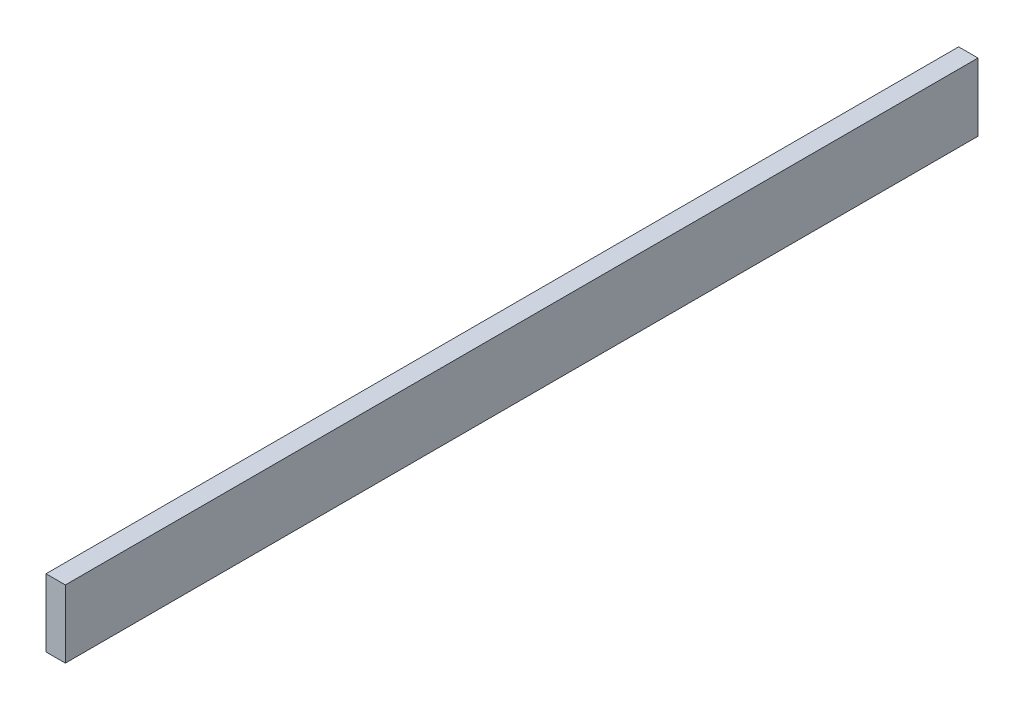
SolidWorks part; units mm, degrees
ref_plane "Front Plane" through (0, 0, 0) normal (0, 0, 1) x (1, 0, 0)
ref_plane "Top Plane" through (0, 0, 0) normal (0, 1, 0) x (1, 0, 0)
ref_plane "Right Plane" through (0, 0, 0) normal (1, 0, 0) x (0, 0, -1)
other "Configuration Table"
sketch "Sketch1" plane through (0, 0, 0) normal (0, 0, 1) x (1, 0, 0)
  line L1 (0, 0) -> (14, 0)
  line L2 (0, 0) -> (0, 49)
  line L3 (0, 49) -> (14, 49)
  line L4 (14, 0) -> (14, 49)
extrude "RAY_DIS_PROFIL_14x49x660_1" add sketch "Sketch1" against normal blind 660 separate body
